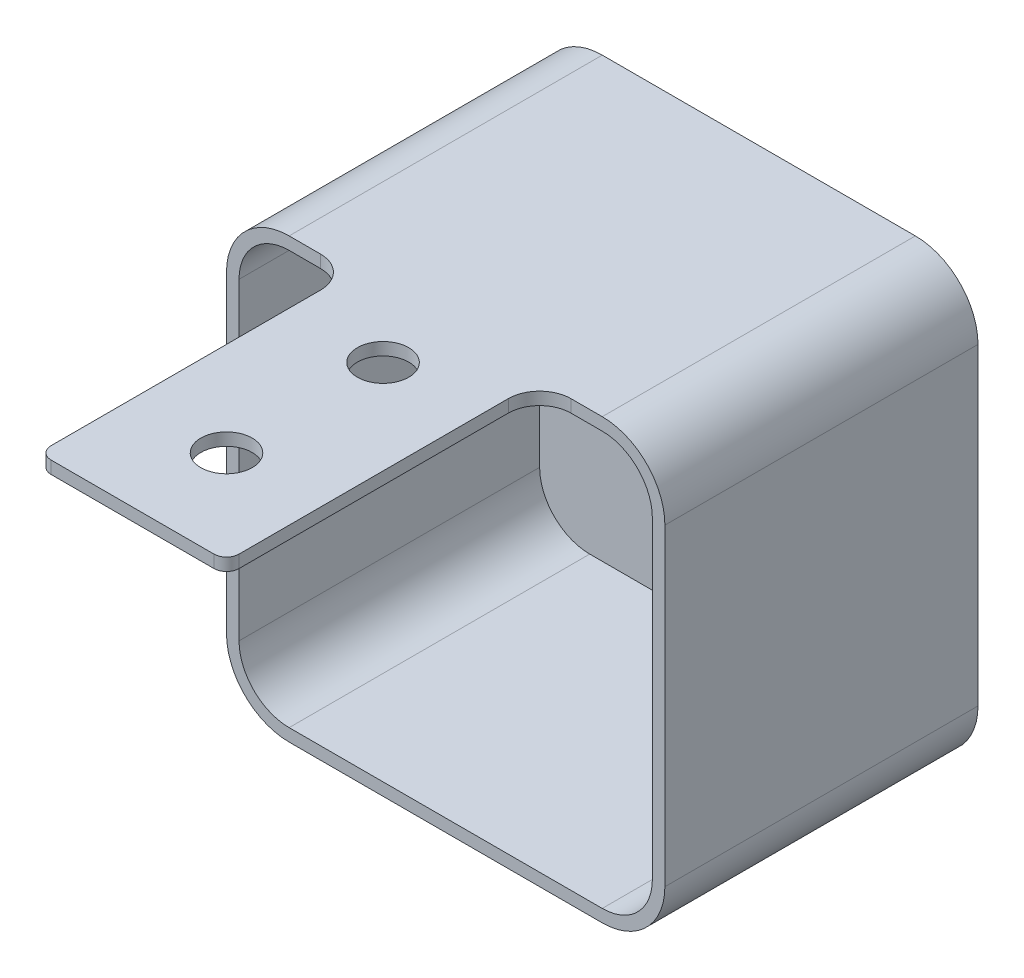
SolidWorks part; units mm, degrees
ref_plane "Front Plane" through (0, 0, 0) normal (0, 0, 1) x (1, 0, 0)
ref_plane "Top Plane" through (0, 0, 0) normal (0, 1, 0) x (1, 0, 0)
ref_plane "Right Plane" through (0, 0, 0) normal (1, 0, 0) x (0, 0, -1)
sketch "Sketch1" plane through (0, 0, 0) normal (0, 0, 1) x (1, 0, 0)
  line L1 (-35, -35) -> (35, -35)
  line L2 (-35, -35) -> (-35, 35)
  line L3 (-35, 35) -> (35, 35)
  line L4 (35, -35) -> (35, 35)
  line L5 (-35, -35) -> (35, 35) construction
  line L6 (-35, 35) -> (35, -35) construction
  point P0 (0, 0)
  dimension "D1" = 70
  dimension "D2" = 70
extrude "Boss-Extrude1" add sketch "Sketch1" along normal blind 50
fillet "Fillet1" radius 10 4 edges at (35, -35, 25) (-35, -35, 25) (-35, 35, 25) (35, 35, 25)
shell "Shell1" thickness 2
sketch "Sketch2" plane through (0, 35, 0) normal (0, 1, 0) x (1, 0, 0)
  line L0 (25, -50) -> (-25, -50) construction
  line L1 (-15, -50) -> (15, -50)
  line L2 (-15, -50) -> (-15, -100)
  line L3 (-15, -100) -> (15, -100)
  line L4 (15, -50) -> (15, -100)
  line L5 (0, 0) -> (0, -50) construction
  line L6 (25, 0) -> (-25, 0) construction
  line L7 (-15, -100) -> (15, -70) construction
  line L8 (0, -85) -> (0, -60) construction
  circle A0 centre (0, -85) radius 4.1
  circle A1 centre (0, -60) radius 4.1
  dimension "D4" = 8.2
  dimension "D1" = 50
  dimension "D2" = 30
  dimension "D3" = 45
  dimension "D5" = 25
extrude "Boss-Extrude2" add sketch "Sketch2" against normal up to surface (2 mm away) up to face at (0, 33, 26)
fillet "Fillet2" radius 5 2 edges
fillet "Fillet3" radius 2 2 edges at (-15, 34, 100) (15, 34, 100)
